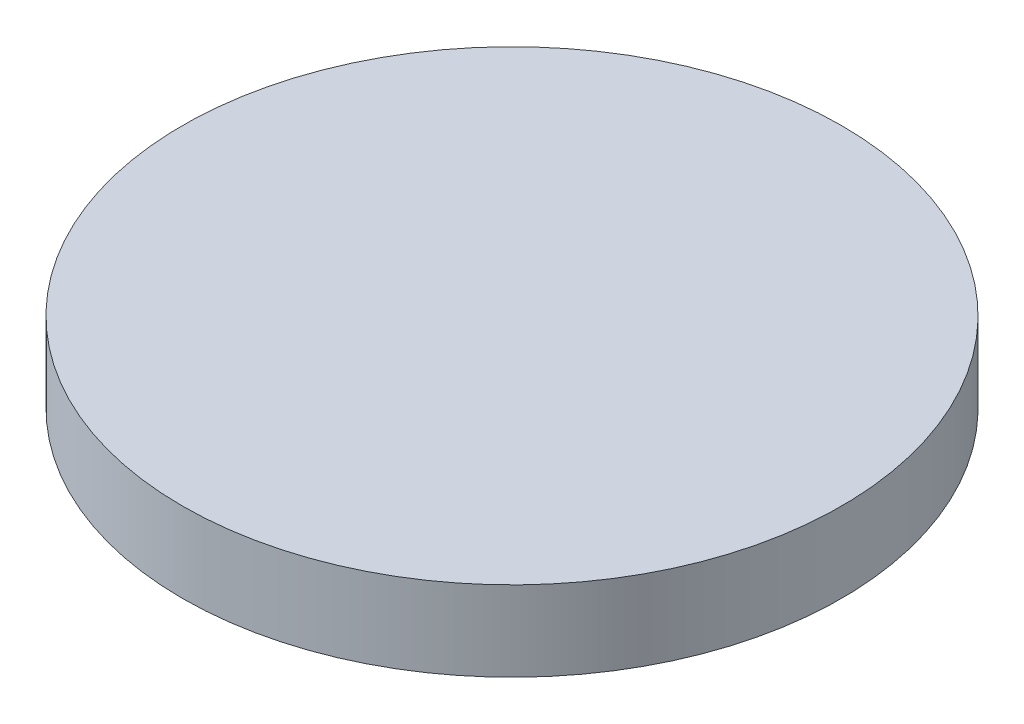
SolidWorks part; units mm, degrees
ref_plane "Front Plane" through (0, 0, 0) normal (0, 0, 1) x (1, 0, 0)
ref_plane "Top Plane" through (0, 0, 0) normal (0, 1, 0) x (1, 0, 0)
ref_plane "Right Plane" through (0, 0, 0) normal (1, 0, 0) x (0, 0, -1)
sketch "Sketch1" plane through (0, 0, 0) normal (0, 1, 0) x (1, 0, 0)
  circle A0 centre (0, 0) radius 30.3355
extrude "Gear 1" add sketch "Sketch1" along normal blind 7.366
